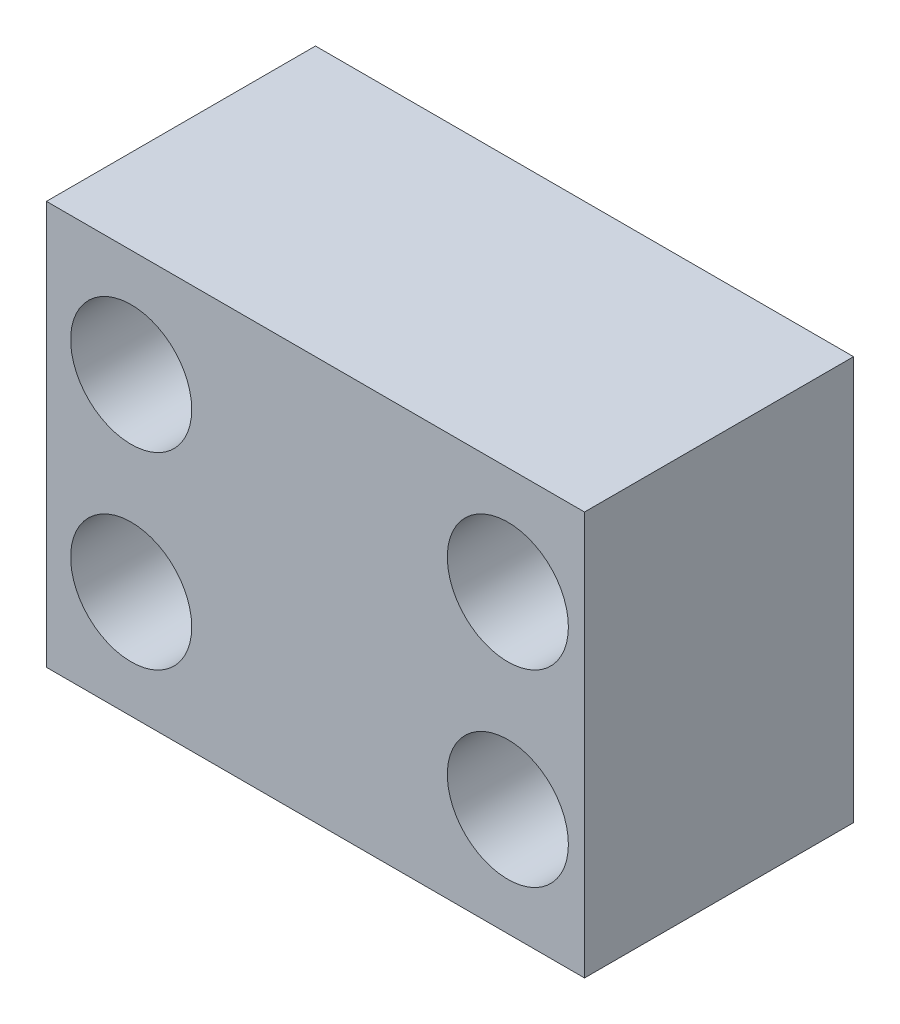
SolidWorks part; units mm, degrees
ref_plane "Front Plane" through (0, 0, 0) normal (0, 0, 1) x (1, 0, 0)
ref_plane "Top Plane" through (0, 0, 0) normal (0, 1, 0) x (1, 0, 0)
ref_plane "Right Plane" through (0, 0, 0) normal (1, 0, 0) x (0, 0, -1)
sketch "Sketch1" plane through (0, 0, 0) normal (0, 0, 1) x (1, 0, 0)
  line L1 (-100, -75) -> (100, -75)
  line L2 (-100, -75) -> (-100, 75)
  line L3 (-100, 75) -> (100, 75)
  line L4 (100, -75) -> (100, 75)
  line L5 (0, 75) -> (0, -75) construction
  line L6 (-100, 0) -> (100, 0) construction
  point P0 (0, 0)
  dimension "D1" = 200
  dimension "D2" = 150
extrude "Boss-Extrude1" add sketch "Sketch1" along normal blind 100
sketch "Sketch2" plane through (0, 0, 100) normal (0, 0, 1) x (1, 0, 0)
  line L0 (100, 75) -> (-100, 75) construction
  line L1 (-100, 75) -> (-100, -75) construction
  line L2 (-100, -75) -> (100, -75) construction
  circle A0 centre (-68.5, 35) radius 22.5
  circle A1 centre (-68.5, -35) radius 22.5
  circle A2 centre (71.5, 35) radius 22.5
  circle A3 centre (71.5, -35) radius 22.5
  dimension "D1" = 45
  dimension "D4" = 31.5
  dimension "D6" = 45
  dimension "D7" = 2
  dimension "D2" = 40
  dimension "D3" = 31.5
  dimension "D5" = 40
extrude "Cut-Extrude1" cut sketch "Sketch2" against normal up to surface (100 mm away) up to face at (0, 0, 0)
